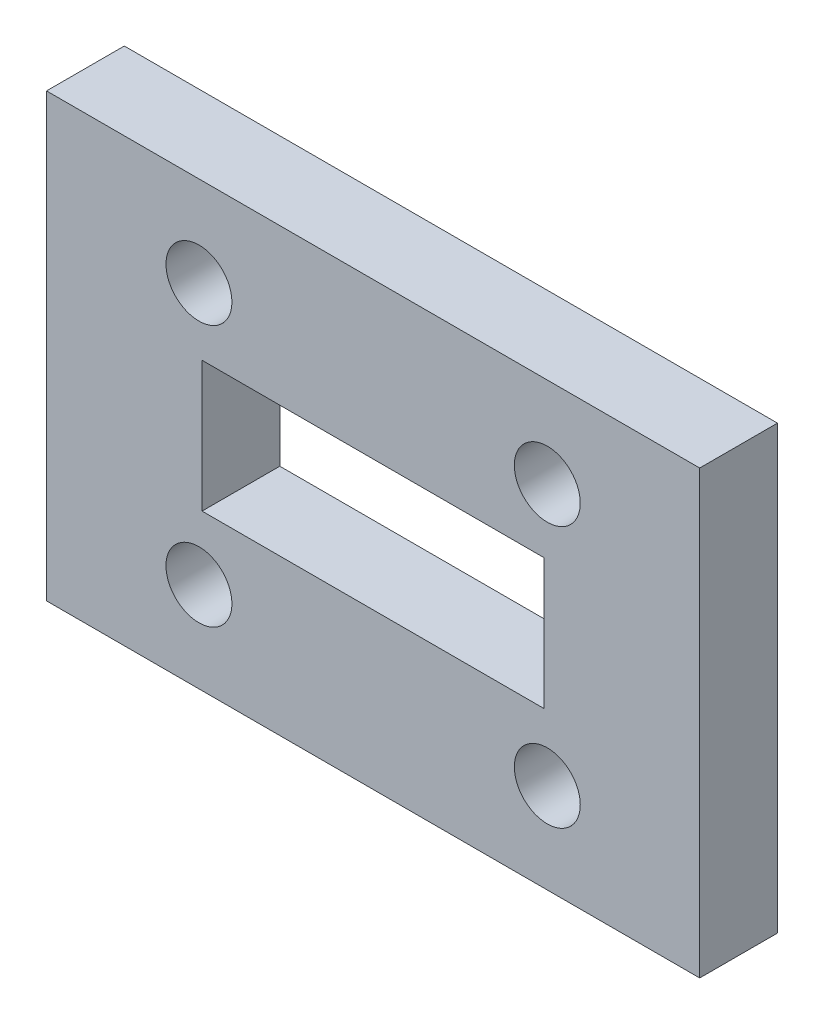
SolidWorks part; units mm, degrees
ref_plane "Front Plane" through (0, 0, 0) normal (0, 0, 1) x (1, 0, 0)
ref_plane "Top Plane" through (0, 0, 0) normal (0, 1, 0) x (1, 0, 0)
ref_plane "Right Plane" through (0, 0, 0) normal (1, 0, 0) x (0, 0, -1)
sketch "Sketch1" plane through (0, 0, 0) normal (0, 0, 1) x (1, 0, 0)
  line L1 (6.985, -2.667) -> (-6.985, -2.667) construction
  line L2 (6.985, -2.667) -> (6.985, 2.667) construction
  line L3 (6.985, 2.667) -> (-6.985, 2.667) construction
  line L4 (-6.985, -2.667) -> (-6.985, 2.667) construction
  line L5 (6.985, -2.667) -> (-6.985, 2.667) construction
  line L6 (6.985, 2.667) -> (-6.985, -2.667) construction
  point P0 (0, 0)
  dimension "D1" = 5.334
  dimension "D2" = 13.97
sketch "Sketch2" plane through (0, 0, 0) normal (0, 0, 1) x (1, 0, 0)
  line L1 (6.985, -2.667) -> (-6.985, -2.667)
  line L2 (6.985, -2.667) -> (6.985, 2.667)
  line L3 (6.985, 2.667) -> (-6.985, 2.667)
  line L4 (-6.985, -2.667) -> (-6.985, 2.667)
  line L5 (6.985, -2.667) -> (-6.985, 2.667) construction
  line L6 (6.985, 2.667) -> (-6.985, -2.667) construction
  line L7 (6.985, -2.667) -> (6.985, 2.667) construction
  line L8 (13.335, -9.017) -> (-13.335, -9.017)
  line L9 (13.335, -9.017) -> (13.335, 9.017)
  line L10 (13.335, 9.017) -> (-13.335, 9.017)
  line L11 (-13.335, -9.017) -> (-13.335, 9.017)
  line L12 (13.335, -9.017) -> (-13.335, 9.017) construction
  line L13 (13.335, 9.017) -> (-13.335, -9.017) construction
  line L14 (6.985, -2.667) -> (-6.985, -2.667) construction
  line L15 (0, 9.017) -> (0, -9.017) construction
  line L16 (-13.335, 0) -> (13.335, 0) construction
  circle A0 centre (-7.112, 5.334) radius 1.3462
  circle A1 centre (7.112, 5.334) radius 1.3462
  circle A2 centre (7.112, -5.334) radius 1.3462
  circle A3 centre (-7.112, -5.334) radius 1.3462
  point P0 (0, 0)
  dimension "D4" = 2.6924
  dimension "D1" = 6.35
  dimension "D2" = 6.35
  dimension "D3" = 7.112
  dimension "D5" = 5.334
extrude "Boss-Extrude1" add sketch "Sketch2" along normal blind 3.175
